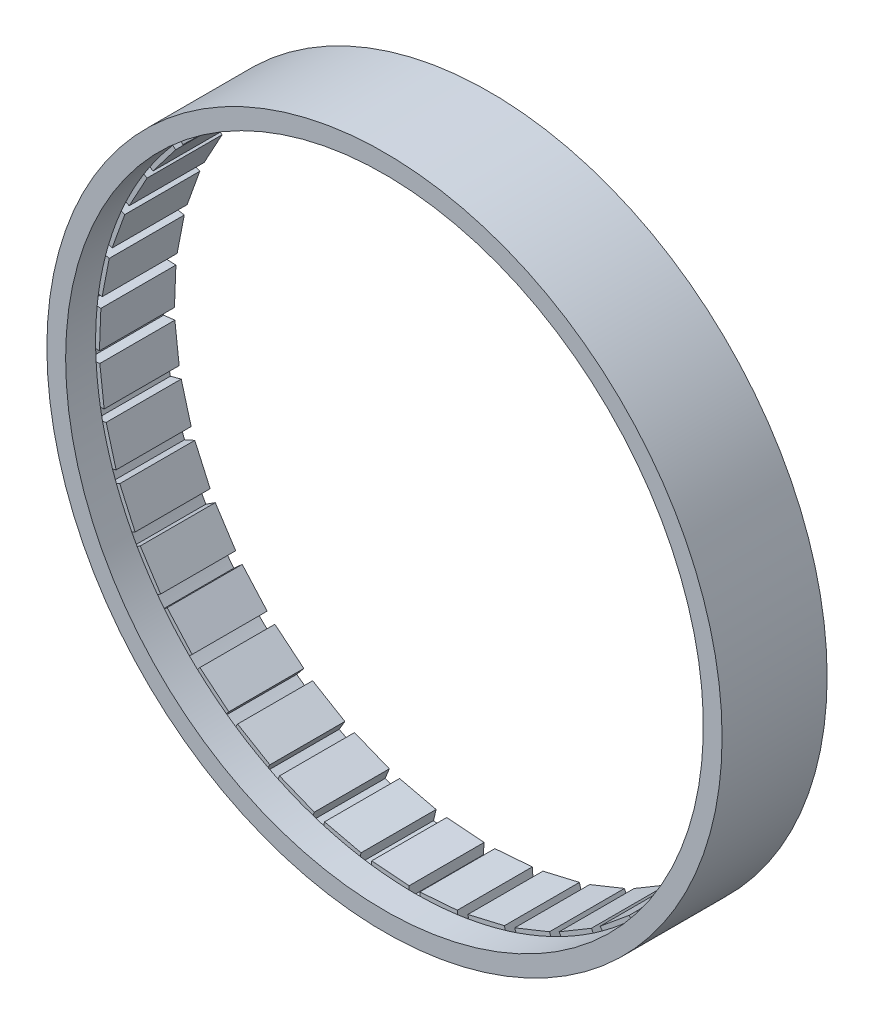
SolidWorks part; units mm, degrees
ref_plane "Front Plane" through (0, 0, 0) normal (0, 0, 1) x (1, 0, 0)
ref_plane "Top Plane" through (0, 0, 0) normal (0, 1, 0) x (1, 0, 0)
ref_plane "Right Plane" through (0, 0, 0) normal (1, 0, 0) x (0, 0, -1)
sketch "Sketch2" plane through (0, 0, 0) normal (1, 0, 0) x (0, 0, -1)
  line L0 (0, 0) -> (-98.2666, 0) construction
  line L1 (0, 45) -> (-14, 45)
  line L2 (-14, 45) -> (-14, 42.5)
  line L3 (-14, 42.5) -> (-10, 42.5)
  line L4 (-10, 42.5) -> (-10, 43.5)
  line L5 (-10, 43.5) -> (0, 43.5)
  line L6 (0, 43.5) -> (0, 45)
  dimension "D1" = 90
  dimension "D2" = 85
  dimension "D3" = 14
  dimension "D4" = 4
  dimension "D5" = 1.5
revolve "Revolve1" add sketch "Sketch2" angle 360 about L0
sketch "Sketch4" plane through (0, 0, 0) normal (0, 0, -1) x (-1, 0, 0)
  line L0 (-2.5, 41.9281) -> (2.5, 41.9281)
  line L1 (2.5, 41.9281) -> (2.5, 43.4281)
  line L2 (-2.5, 41.9281) -> (-2.5, 43.4281)
  line L3 (3.9296, 41.8183) -> (4.1586, 43.3008)
  line L4 (8.871, 41.0551) -> (9.1, 42.5375)
  line L5 (3.9296, 41.8183) -> (8.871, 41.0551)
  line L6 (10.2671, 40.7284) -> (10.7197, 42.1585)
  line L7 (15.0341, 39.2198) -> (15.4866, 40.6499)
  line L8 (10.2671, 40.7284) -> (15.0341, 39.2198)
  line L9 (16.3639, 38.6838) -> (17.0295, 40.0281)
  line L10 (20.8447, 36.4652) -> (21.5103, 37.8095)
  line L11 (16.3639, 38.6838) -> (20.8447, 36.4652)
  line L12 (22.0772, 35.7325) -> (22.9402, 36.9594)
  line L13 (26.1668, 32.8559) -> (27.0298, 34.0828)
  line L14 (22.0772, 35.7325) -> (26.1668, 32.8559)
  line L15 (27.273, 31.9437) -> (28.3132, 33.0245)
  line L16 (30.8756, 28.4765) -> (31.9158, 29.5573)
  line L17 (27.273, 31.9437) -> (30.8756, 28.4765)
  line L18 (31.8296, 27.4061) -> (33.0225, 28.3155)
  line L19 (34.8607, 23.4296) -> (36.0536, 24.339)
  line L20 (31.8296, 27.4061) -> (34.8607, 23.4296)
  line L21 (35.6401, 22.2262) -> (36.9578, 22.9427)
  line L22 (38.0287, 17.8336) -> (39.3464, 18.5502)
  line L23 (35.6401, 22.2262) -> (38.0287, 17.8336)
  line L24 (38.6152, 16.5253) -> (40.0269, 17.0323)
  line L25 (40.3053, 11.8196) -> (41.717, 12.3266)
  line L26 (38.6152, 16.5253) -> (40.3053, 11.8196)
  line L27 (40.6852, 10.437) -> (42.1578, 10.7226)
  line L28 (41.6371, 5.5285) -> (43.1097, 5.8141)
  line L29 (40.6852, 10.437) -> (41.6371, 5.5285)
  line L30 (41.8016, 4.1041) -> (43.3005, 4.1616)
  line L31 (41.9931, -0.8922) -> (43.492, -0.8348)
  line L32 (41.8016, 4.1041) -> (41.9931, -0.8922)
  line L33 (41.9382, -2.325) -> (43.4283, -2.497)
  line L34 (41.3648, -7.292) -> (42.8549, -7.464)
  line L35 (41.9382, -2.325) -> (41.3648, -7.292)
  line L36 (41.0918, -8.6995) -> (42.5382, -9.097)
  line L37 (39.7669, -13.5208) -> (41.2132, -13.9183)
  line L38 (41.0918, -8.6995) -> (39.7669, -13.5208)
  line L39 (39.2822, -14.8702) -> (40.651, -15.4838)
  line L40 (37.2369, -19.4327) -> (38.6056, -20.0463)
  line L41 (39.2822, -14.8702) -> (37.2369, -19.4327)
  line L42 (36.5519, -20.6923) -> (37.811, -21.5077)
  line L43 (33.8341, -24.8892) -> (35.0931, -25.7045)
  line L44 (36.5519, -20.6923) -> (33.8341, -24.8892)
  line L45 (32.9649, -26.0295) -> (34.0847, -27.0274)
  line L46 (29.6382, -29.7622) -> (30.7581, -30.7602)
  line L47 (32.9649, -26.0295) -> (29.6382, -29.7622)
  line L48 (28.6052, -30.7565) -> (29.5595, -31.9137)
  line L49 (24.7477, -33.9377) -> (25.7021, -35.0949)
  line L50 (28.6052, -30.7565) -> (24.7477, -33.9377)
  line L51 (23.575, -34.7626) -> (24.3415, -36.0519)
  line L52 (19.2771, -37.3177) -> (20.0436, -38.607)
  line L53 (23.575, -34.7626) -> (19.2771, -37.3177)
  line L54 (17.9922, -37.9539) -> (18.5529, -39.3451)
  line L55 (13.3547, -39.823) -> (13.9154, -41.2142)
  line L56 (17.9922, -37.9539) -> (13.3547, -39.823)
  line L57 (11.9877, -40.2556) -> (12.3295, -41.7161)
  line L58 (7.1192, -41.3948) -> (7.461, -42.8554)
  line L59 (11.9877, -40.2556) -> (7.1192, -41.3948)
  line L60 (5.7022, -41.6137) -> (5.8171, -43.1093)
  line L61 (0.7169, -41.9964) -> (0.8317, -43.492)
  line L62 (5.7022, -41.6137) -> (0.7169, -41.9964)
  line L63 (-0.7169, -41.9964) -> (-0.8317, -43.492)
  line L64 (-5.7022, -41.6137) -> (-5.8171, -43.1093)
  line L65 (-0.7169, -41.9964) -> (-5.7022, -41.6137)
  line L66 (-7.1192, -41.3948) -> (-7.461, -42.8554)
  line L67 (-11.9877, -40.2556) -> (-12.3295, -41.7161)
  line L68 (-7.1192, -41.3948) -> (-11.9877, -40.2556)
  line L69 (-13.3547, -39.823) -> (-13.9154, -41.2142)
  line L70 (-17.9922, -37.9539) -> (-18.5529, -39.3451)
  line L71 (-13.3547, -39.823) -> (-17.9922, -37.9539)
  line L72 (-19.2771, -37.3177) -> (-20.0436, -38.607)
  line L73 (-23.575, -34.7626) -> (-24.3415, -36.0519)
  line L74 (-19.2771, -37.3177) -> (-23.575, -34.7626)
  line L75 (-24.7477, -33.9377) -> (-25.7021, -35.0949)
  line L76 (-28.6052, -30.7565) -> (-29.5595, -31.9137)
  line L77 (-24.7477, -33.9377) -> (-28.6052, -30.7565)
  line L78 (-29.6382, -29.7622) -> (-30.7581, -30.7602)
  line L79 (-32.9649, -26.0295) -> (-34.0847, -27.0274)
  line L80 (-29.6382, -29.7622) -> (-32.9649, -26.0295)
  line L81 (-33.8341, -24.8892) -> (-35.0931, -25.7045)
  line L82 (-36.5519, -20.6923) -> (-37.811, -21.5077)
  line L83 (-33.8341, -24.8892) -> (-36.5519, -20.6923)
  line L84 (-37.2369, -19.4327) -> (-38.6056, -20.0463)
  line L85 (-39.2822, -14.8702) -> (-40.651, -15.4838)
  line L86 (-37.2369, -19.4327) -> (-39.2822, -14.8702)
  line L87 (-39.7669, -13.5208) -> (-41.2132, -13.9183)
  line L88 (-41.0918, -8.6995) -> (-42.5382, -9.097)
  line L89 (-39.7669, -13.5208) -> (-41.0918, -8.6995)
  line L90 (-41.3648, -7.292) -> (-42.8549, -7.464)
  line L91 (-41.9382, -2.325) -> (-43.4283, -2.497)
  line L92 (-41.3648, -7.292) -> (-41.9382, -2.325)
  line L93 (-41.9931, -0.8922) -> (-43.492, -0.8348)
  line L94 (-41.8016, 4.1041) -> (-43.3005, 4.1616)
  line L95 (-41.9931, -0.8922) -> (-41.8016, 4.1041)
  line L96 (-41.6371, 5.5285) -> (-43.1097, 5.8141)
  line L97 (-40.6852, 10.437) -> (-42.1578, 10.7226)
  line L98 (-41.6371, 5.5285) -> (-40.6852, 10.437)
  line L99 (-40.3053, 11.8196) -> (-41.717, 12.3266)
  line L100 (-38.6152, 16.5253) -> (-40.0269, 17.0323)
  line L101 (-40.3053, 11.8196) -> (-38.6152, 16.5253)
  line L102 (-38.0287, 17.8336) -> (-39.3464, 18.5502)
  line L103 (-35.6401, 22.2262) -> (-36.9578, 22.9427)
  line L104 (-38.0287, 17.8336) -> (-35.6401, 22.2262)
  line L105 (-34.8607, 23.4296) -> (-36.0536, 24.339)
  line L106 (-31.8296, 27.4061) -> (-33.0225, 28.3155)
  line L107 (-34.8607, 23.4296) -> (-31.8296, 27.4061)
  line L108 (-30.8756, 28.4765) -> (-31.9158, 29.5573)
  line L109 (-27.273, 31.9437) -> (-28.3132, 33.0245)
  line L110 (-30.8756, 28.4765) -> (-27.273, 31.9437)
  line L111 (-26.1668, 32.8559) -> (-27.0298, 34.0828)
  line L112 (-22.0772, 35.7325) -> (-22.9402, 36.9594)
  line L113 (-26.1668, 32.8559) -> (-22.0772, 35.7325)
  line L114 (-20.8447, 36.4652) -> (-21.5103, 37.8095)
  line L115 (-16.3639, 38.6838) -> (-17.0295, 40.0281)
  line L116 (-20.8447, 36.4652) -> (-16.3639, 38.6838)
  line L117 (-15.0341, 39.2198) -> (-15.4866, 40.6499)
  line L118 (-10.2671, 40.7284) -> (-10.7197, 42.1585)
  line L119 (-15.0341, 39.2198) -> (-10.2671, 40.7284)
  line L120 (-8.871, 41.0551) -> (-9.1, 42.5375)
  line L121 (-3.9296, 41.8183) -> (-4.1586, 43.3008)
  line L122 (-8.871, 41.0551) -> (-3.9296, 41.8183)
  arc A0 (-2.5, 43.4281) -> (2.5, 43.4281) centre (0, 0) cw
  circle A1 centre (0, 0) radius 43.5 construction
  arc A2 (4.1586, 43.3008) -> (9.1, 42.5375) centre (0, 0) cw
  arc A3 (10.7197, 42.1585) -> (15.4866, 40.6499) centre (0, 0) cw
  arc A4 (17.0295, 40.0281) -> (21.5103, 37.8095) centre (0, 0) cw
  arc A5 (22.9402, 36.9594) -> (27.0298, 34.0828) centre (0, 0) cw
  arc A6 (28.3132, 33.0245) -> (31.9158, 29.5573) centre (0, 0) cw
  arc A7 (33.0225, 28.3155) -> (36.0536, 24.339) centre (0, 0) cw
  arc A8 (36.9578, 22.9427) -> (39.3464, 18.5502) centre (0, 0) cw
  arc A9 (40.0269, 17.0323) -> (41.717, 12.3266) centre (0, 0) cw
  arc A10 (42.1578, 10.7226) -> (43.1097, 5.8141) centre (0, 0) cw
  arc A11 (43.3005, 4.1616) -> (43.492, -0.8348) centre (0, 0) cw
  arc A12 (43.4283, -2.497) -> (42.8549, -7.464) centre (0, 0) cw
  arc A13 (42.5382, -9.097) -> (41.2132, -13.9183) centre (0, 0) cw
  arc A14 (40.651, -15.4838) -> (38.6056, -20.0463) centre (0, 0) cw
  arc A15 (37.811, -21.5077) -> (35.0931, -25.7045) centre (0, 0) cw
  arc A16 (34.0847, -27.0274) -> (30.7581, -30.7602) centre (0, 0) cw
  arc A17 (29.5595, -31.9137) -> (25.7021, -35.0949) centre (0, 0) cw
  arc A18 (24.3415, -36.0519) -> (20.0436, -38.607) centre (0, 0) cw
  arc A19 (18.5529, -39.3451) -> (13.9154, -41.2142) centre (0, 0) cw
  arc A20 (12.3295, -41.7161) -> (7.461, -42.8554) centre (0, 0) cw
  arc A21 (5.8171, -43.1093) -> (0.8317, -43.492) centre (0, 0) cw
  arc A22 (-0.8317, -43.492) -> (-5.8171, -43.1093) centre (0, 0) cw
  arc A23 (-7.461, -42.8554) -> (-12.3295, -41.7161) centre (0, 0) cw
  arc A24 (-13.9154, -41.2142) -> (-18.5529, -39.3451) centre (0, 0) cw
  arc A25 (-20.0436, -38.607) -> (-24.3415, -36.0519) centre (0, 0) cw
  arc A26 (-25.7021, -35.0949) -> (-29.5595, -31.9137) centre (0, 0) cw
  arc A27 (-30.7581, -30.7602) -> (-34.0847, -27.0274) centre (0, 0) cw
  arc A28 (-35.0931, -25.7045) -> (-37.811, -21.5077) centre (0, 0) cw
  arc A29 (-38.6056, -20.0463) -> (-40.651, -15.4838) centre (0, 0) cw
  arc A30 (-41.2132, -13.9183) -> (-42.5382, -9.097) centre (0, 0) cw
  arc A31 (-42.8549, -7.464) -> (-43.4283, -2.497) centre (0, 0) cw
  arc A32 (-43.492, -0.8348) -> (-43.3005, 4.1616) centre (0, 0) cw
  arc A33 (-43.1097, 5.8141) -> (-42.1578, 10.7226) centre (0, 0) cw
  arc A34 (-41.717, 12.3266) -> (-40.0269, 17.0323) centre (0, 0) cw
  arc A35 (-39.3464, 18.5502) -> (-36.9578, 22.9427) centre (0, 0) cw
  arc A36 (-36.0536, 24.339) -> (-33.0225, 28.3155) centre (0, 0) cw
  arc A37 (-31.9158, 29.5573) -> (-28.3132, 33.0245) centre (0, 0) cw
  arc A38 (-27.0298, 34.0828) -> (-22.9402, 36.9594) centre (0, 0) cw
  arc A39 (-21.5103, 37.8095) -> (-17.0295, 40.0281) centre (0, 0) cw
  arc A40 (-15.4866, 40.6499) -> (-10.7197, 42.1585) centre (0, 0) cw
  arc A41 (-9.1, 42.5375) -> (-4.1586, 43.3008) centre (0, 0) cw
  point P171 (0, 0)
  dimension "D1" = 5
  dimension "D2" = 1.5
  dimension "D3" = 41
extrude "Boss-Extrude1" add sketch "Sketch4" against normal up to surface (10 mm away) up to face at (-43.5, 0, 10)
